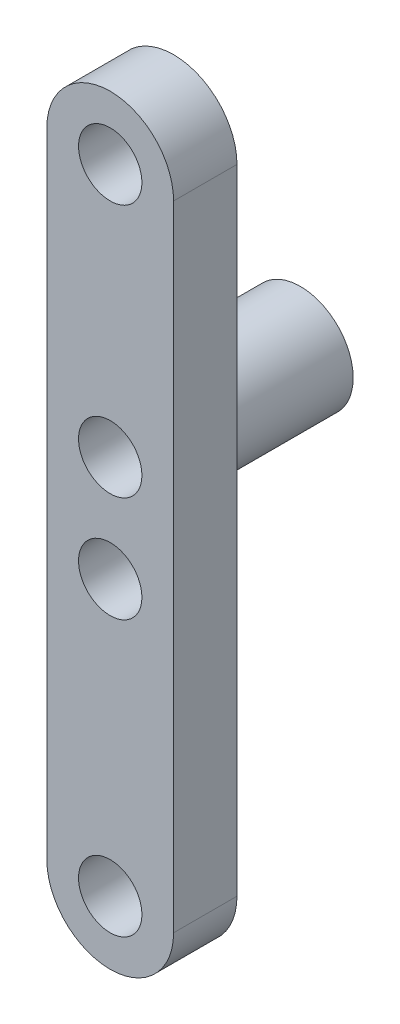
SolidWorks part; units mm, degrees
material "ﾎﾟﾘｵｷｼﾒﾁﾚﾝ(POM)ｱｾﾀｰﾙ共重合体"
ref_plane "正面" through (0, 0, 0) normal (0, 0, 1) x (1, 0, 0)
ref_plane "平面" through (0, 0, 0) normal (0, 1, 0) x (1, 0, 0)
ref_plane "右側面" through (0, 0, 0) normal (1, 0, 0) x (0, 0, -1)
sketch "ｽｹｯﾁ1" plane through (0, 0, 0) normal (0, 0, 1) x (1, 0, 0)
  line L0 (0, 0) -> (0, -30) construction
  line L1 (-3, 0) -> (-3, -30)
  line L2 (3, 0) -> (3, -30)
  line L3 (0, -15) -> (-3, -15) construction
  circle A0 centre (0, 0) radius 1.5
  arc A1 (3, 0) -> (-3, 0) centre (0, 0) ccw
  circle A2 centre (0, -30) radius 1.5
  arc A3 (3, -30) -> (-3, -30) centre (0, -30) cw
  arc A4 (0, -3) -> (3, 0) centre (0, 0) ccw construction
  arc A5 (-3, 0) -> (0, -3) centre (0, 0) ccw construction
  arc A6 (-3, -30) -> (0, -27) centre (0, -30) cw construction
  arc A7 (0, -27) -> (3, -30) centre (0, -30) cw construction
  circle A8 centre (0, -17) radius 1.5
  circle A9 centre (0, -12) radius 1.5
  dimension "D1" = 3
  dimension "D2" = 6
  dimension "D5" = 3
  dimension "D7" = 3
  dimension "D3" = 6
  dimension "D4" = 30
  dimension "D6" = 13
  dimension "D8" = 12
extrude "ﾎﾞｽ - 押し出し1" add sketch "ｽｹｯﾁ1" along normal blind 3
sketch "ｽｹｯﾁ3" plane through (0, 0, 0) normal (0, 0, 1) x (1, 0, 0)
  circle A0 centre (0, -12) radius 2.5
  circle A1 centre (0, -12) radius 1.5 construction
  circle A2 centre (0, -12) radius 1.5
  dimension "D1" = 5
extrude "ﾎﾞｽ - 押し出し2" add sketch "ｽｹｯﾁ3" against normal blind 6 separate body
